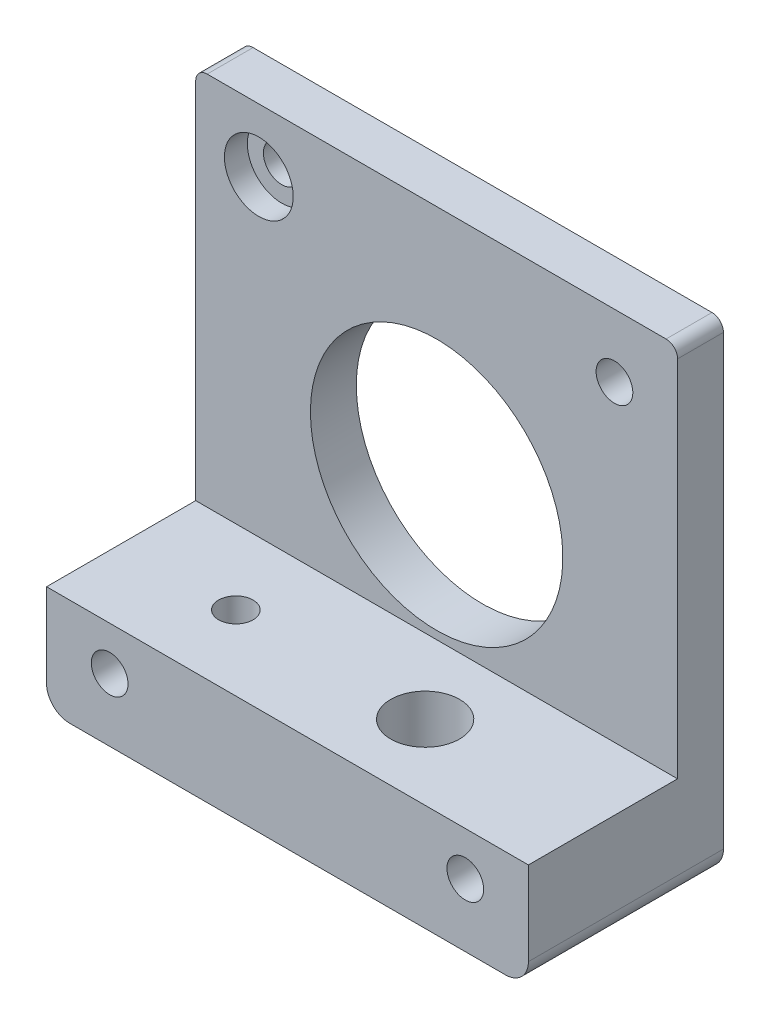
SolidWorks part; units mm, degrees
ref_plane "Front Plane" through (0, 0, 0) normal (0, 0, 1) x (1, 0, 0)
ref_plane "Top Plane" through (0, 0, 0) normal (0, 1, 0) x (1, 0, 0)
ref_plane "Right Plane" through (0, 0, 0) normal (1, 0, 0) x (0, 0, -1)
ref_plane "Plane1" through (0, 0, -8.5) normal (0, 0, -1) x (-1, 0, 0)
sketch "Sketch1" plane through (0, 0, -8.5) normal (0, 0, -1) x (-1, 0, 0)
  line L0 (24.1968, -22.3035) -> (24.1968, 19.6965)
  line L1 (24.1968, 19.6965) -> (-17.8032, 19.6965)
  line L2 (-17.8032, 19.6965) -> (-17.8032, -22.3035)
  line L3 (-17.8032, -22.3035) -> (24.1968, -22.3035)
extrude "Boss-Extrude1" add sketch "Sketch1" against normal blind 17
sketch "Sketch2" plane through (17.8032, 0, 0) normal (1, 0, 0) x (0, 0, -1)
  line L0 (-8.5, -13.0035) -> (4.5, -13.0035)
  line L1 (4.5, -13.0035) -> (4.5, 19.6965)
  line L2 (4.5, 19.6965) -> (-8.5, 19.6965)
  line L3 (-8.5, 19.6965) -> (-8.5, -13.0035)
extrude "Cut-Extrude1" cut sketch "Sketch2" against normal through all
hole_wizard "Ø22.0 (22) Diameter Hole1" positions "Sketch4" profile "Sketch3" hole size "Ø22.0" standard "ANSI Metric"
sketch "Sketch4" plane through (0, 0, -8.5) normal (0, 0, -1) x (-1, 0, 0)
  point P0 (3.1968, -1.3035)
sketch "Sketch3" plane through (-3.1968, -1.3035, -8.5) normal (1, 0, 0) x (0, 1, 0)
  line L0 (0, 0) -> (0, 17)
  line L1 (0, 17) -> (11, 17)
  line L2 (11, 17) -> (11, 0)
  line L5 (11, 0) -> (0, 0)
  line L11 (0, -6.35) -> (0, 107.95) construction
  dimension "Thru Hole Dia." = 22
  dimension "Thru Hole Depth" = 17
hole_wizard "Ø3.2 (3.2) Diameter Hole1" positions "Sketch6" profile "Sketch5" hole size "Ø3.2" standard "ANSI Metric"
sketch "Sketch6" plane through (0, 0, -8.5) normal (0, 0, -1) x (-1, 0, 0)
  point P0 (-12.3032, 14.1965)
sketch "Sketch5" plane through (12.3032, 14.1965, -8.5) normal (1, 0, 0) x (0, 1, 0)
  line L0 (0, 0) -> (0, 17)
  line L1 (0, 17) -> (1.6, 17)
  line L2 (1.6, 17) -> (1.6, 0)
  line L5 (1.6, 0) -> (0, 0)
  line L11 (0, -6.35) -> (0, 107.95) construction
  dimension "Thru Hole Dia." = 3.2
  dimension "Thru Hole Depth" = 17
hole_wizard "Ø3.2 (3.2) Diameter Hole2" positions "Sketch8" profile "Sketch7" hole size "Ø3.2" standard "ANSI Metric"
sketch "Sketch8" plane through (0, 0, 8.5) normal (0, 0, 1) x (1, 0, 0)
  point P0 (-18.6968, -16.8035)
  point P1 (12.3032, -16.8035)
sketch "Sketch7" plane through (-18.6968, -16.8035, 8.5) normal (1, 0, 0) x (0, -1, 0)
  line L0 (0, 0) -> (0, 17)
  line L1 (0, 17) -> (1.6, 17)
  line L2 (1.6, 17) -> (1.6, 0)
  line L5 (1.6, 0) -> (0, 0)
  line L11 (0, -6.35) -> (0, 107.95) construction
  dimension "Thru Hole Dia." = 3.2
  dimension "Thru Hole Depth" = 17
hole_wizard "Ø6.0 (6) Diameter Hole1" positions "Sketch10" profile "Sketch9" hole size "Ø6.0" standard "ANSI Metric"
sketch "Sketch10" plane through (0, -22.3035, 0) normal (0, -1, 0) x (-1, 0, 0)
  line L0 (-17.8032, -8.5) -> (24.1968, -8.5) construction
  line L1 (-17.8032, -8.5) -> (-17.8032, 8.5) construction
  point P0 (-2.3032, -2)
  dimension "D1" = 6.5
  dimension "D2" = 15.5
sketch "Sketch9" plane through (2.3032, -22.3035, 2) normal (1, 0, 0) x (0, 0, -1)
  line L0 (0, 0) -> (0, 42)
  line L1 (0, 42) -> (3, 42)
  line L2 (3, 42) -> (3, 0)
  line L5 (3, 0) -> (0, 0)
  line L11 (0, -6.35) -> (0, 107.95) construction
  dimension "Thru Hole Dia." = 6
  dimension "Thru Hole Depth" = 42
hole_wizard "Ø3.0 (3) Diameter Hole1" positions "Sketch12" profile "Sketch11" hole size "Ø3.0" standard "ANSI Metric"
sketch "Sketch12" plane through (0, -22.3035, 0) normal (0, -1, 0) x (-1, 0, 0)
  line L0 (24.1968, -8.5) -> (24.1968, 8.5) construction
  line L1 (-17.8032, -8.5) -> (24.1968, -8.5) construction
  point P0 (14.1968, -2)
  dimension "D1" = 10
  dimension "D2" = 6.5
sketch "Sketch11" plane through (-14.1968, -22.3035, 2) normal (1, 0, 0) x (0, 0, -1)
  line L0 (0, 0) -> (0, 42)
  line L1 (0, 42) -> (1.5, 42)
  line L2 (1.5, 42) -> (1.5, 0)
  line L5 (1.5, 0) -> (0, 0)
  line L11 (0, -6.35) -> (0, 107.95) construction
  dimension "Thru Hole Dia." = 3
  dimension "Thru Hole Depth" = 42
hole_wizard "CBORE for M3 Hex Head Machine Screw1" positions "Sketch14" profile "Sketch13" counterbore size "M3" standard "ANSI Metric"
sketch "Sketch14" plane through (0, 0, -4.5) normal (0, 0, 1) x (1, 0, 0)
  point P0 (-18.6968, 14.1965)
sketch "Sketch13" plane through (-18.6968, 14.1965, -4.5) normal (1, 0, 0) x (0, -1, 0)
  line L0 (0, 0) -> (0, 4)
  line L1 (0, 4) -> (1.6, 4)
  line L3 (1.6, 4) -> (1.6, 2)
  line L4 (1.6, 2) -> (3, 2)
  line L5 (3, 2) -> (3, 0)
  line L7 (3, 0) -> (0, 0)
  line L11 (0, -6.35) -> (0, 107.95) construction
  dimension "Thru Hole Dia." = 3.2
  dimension "Thru Hole Depth" = 4
  dimension "C'Bore Dia." = 6
  dimension "C'Bore Depth" = 2
fillet "Fillet1" radius 1 2 edges at (-24.1968, 19.6965, -6.5) (17.8032, 19.6965, -6.5)
fillet "Fillet2" radius 2 2 edges at (-24.1968, -22.3035, 0) (17.8032, -22.3035, 0)
sketch "Sketch15" plane through (0, 0, 0) normal (0, 1, 0) x (1, 0, 0)
  line L0 (2.3032, 1) -> (2.3032, -5) construction
  line L1 (-0.6968, -2) -> (5.3032, -2) construction
  circle A0 centre (2.3032, -2) radius 3 construction
  circle A1 centre (2.3032, -2) radius 1.5
  dimension "D1" = 3
